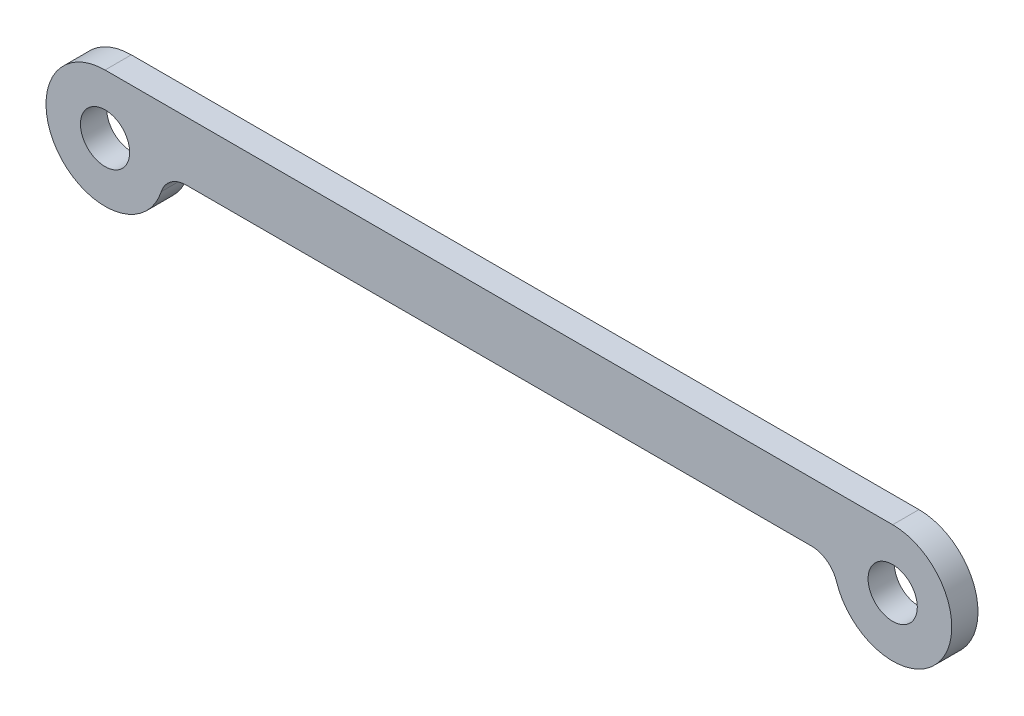
SolidWorks part; units mm, degrees
ref_plane "Front Plane" through (0, 0, 0) normal (0, 0, 1) x (1, 0, 0)
ref_plane "Top Plane" through (0, 0, 0) normal (0, 1, 0) x (1, 0, 0)
ref_plane "Right Plane" through (0, 0, 0) normal (1, 0, 0) x (0, 0, -1)
sketch "Sketch1" plane through (0, 0, 0) normal (0, 0, 1) x (1, 0, 0)
  line L8 (0, 4.5) -> (60, 4.5)
  line L10 (0, 0) -> (60, 0) construction
  line L12 (53.8153, 0) -> (6.1847, 0)
  line L15 (0, 0) -> (6.4952, 3.75) construction
  line L17 (60, 0) -> (53.5048, 3.75) construction
  arc A0 (55.7183, -1.3846) -> (53.8153, 0) centre (53.8153, -2) ccw
  arc A1 (4.2817, -1.3846) -> (6.1847, 0) centre (6.1847, -2) cw
  circle A8 centre (0, 0) radius 1.875
  arc A9 (0, 4.5) -> (4.2817, -1.3846) centre (0, 0) ccw
  circle A10 centre (60, 0) radius 1.875
  arc A11 (55.7183, -1.3846) -> (60, 4.5) centre (60, 0) ccw
  dimension "D2" = 2
  dimension "D7" = 3.75
  dimension "D8" = 9
  dimension "D9" = 9
  dimension "D10" = 3.75
  dimension "D11" = 4.5
  dimension "D14" = 60
  dimension "D16" = 30
  dimension "D17" = 30
extrude "Boss-Extrude1" add sketch "Sketch1" along normal blind 2
